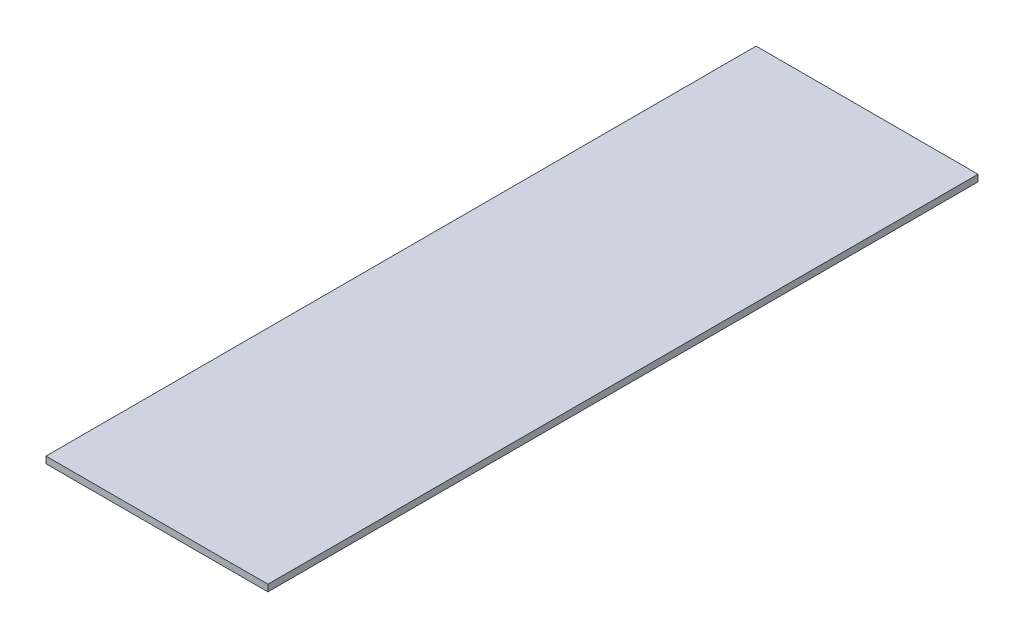
SolidWorks part; units mm, degrees
ref_plane "Front Plane" through (0, 0, 0) normal (0, 0, 1) x (1, 0, 0)
ref_plane "Top Plane" through (0, 0, 0) normal (0, 1, 0) x (1, 0, 0)
ref_plane "Right Plane" through (0, 0, 0) normal (1, 0, 0) x (0, 0, -1)
sketch "Sketch1" plane through (0, 0, 0) normal (0, 1, 0) x (1, 0, 0)
  line L1 (-50, 160) -> (50, 160)
  line L2 (-50, 160) -> (-50, -160)
  line L3 (-50, -160) -> (50, -160)
  line L4 (50, 160) -> (50, -160)
  line L5 (-50, 160) -> (50, -160) construction
  line L6 (-50, -160) -> (50, 160) construction
  point P0 (0, 0)
  dimension "D1" = 320
  dimension "D2" = 100
extrude "Sides" add sketch "Sketch1" along normal blind 3
